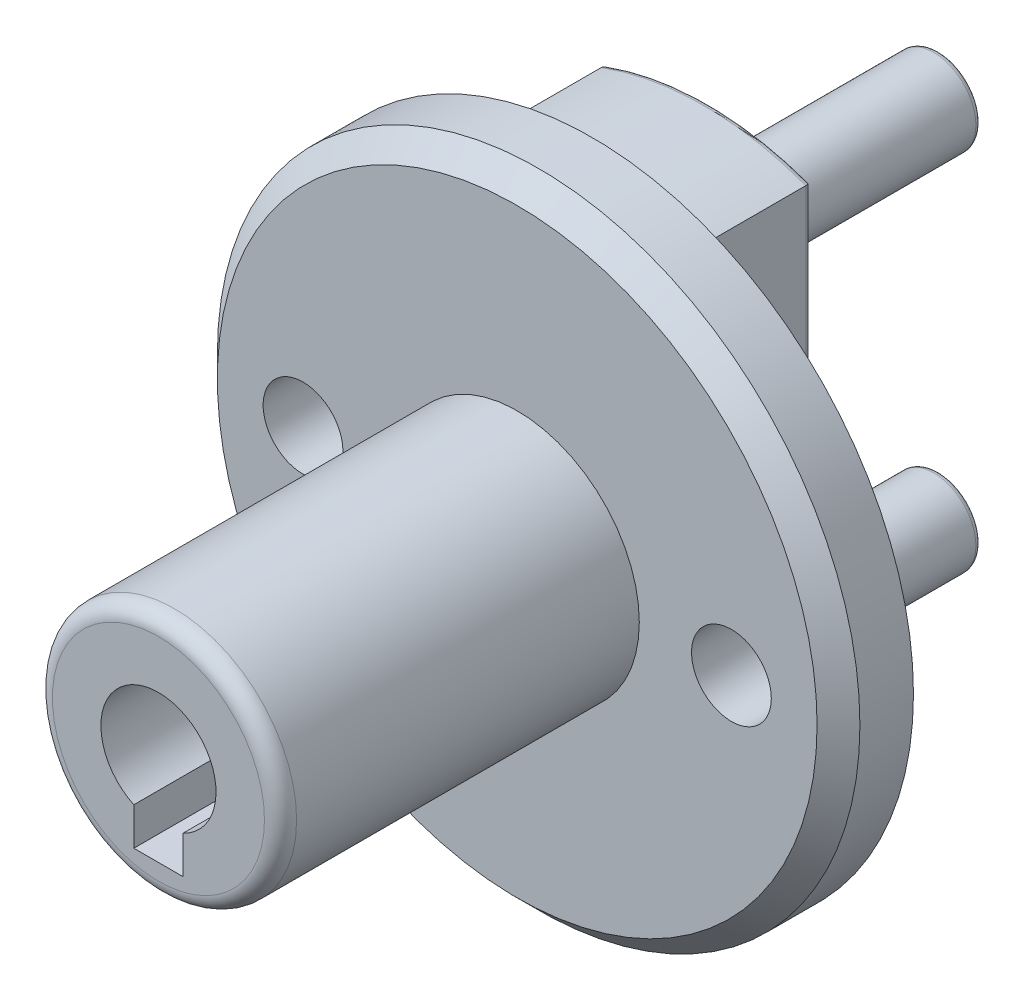
SolidWorks part; units mm, degrees
material "Custom Plastic"
ref_plane "X-Y Datum" through (0, 0, 0) normal (0, 0, 1) x (1, 0, 0)
ref_plane "X-Z Datum" through (0, 0, 0) normal (0, 1, 0) x (1, 0, 0)
ref_plane "Y-Z Datum" through (0, 0, 0) normal (1, 0, 0) x (0, 0, -1)
sketch "Sketch2" plane through (0, 0, 0) normal (0, 0, 1) x (1, 0, 0)
  circle A0 centre (0, 0) radius 30
  dimension "D1" = 60
extrude "Boss-Extrude1" add sketch "Sketch2" along normal blind 7
sketch "Sketch3" plane through (0, 0, 7) normal (0, 0, 1) x (1, 0, 0)
  circle A0 centre (0, 0) radius 11.4
  dimension "D1" = 22.8
extrude "Boss-Extrude2" add sketch "Sketch3" along normal blind 33.5
sketch "Sketch4" plane through (0, 0, 0) normal (0, 0, -1) x (-1, 0, 0)
  line L1 (-9.55, 25.6819) -> (9.55, 25.6819)
  line L2 (-9.55, 25.6819) -> (-9.55, -25.6819)
  line L3 (-9.55, -25.6819) -> (9.55, -25.6819)
  line L4 (9.55, 25.6819) -> (9.55, -25.6819)
  line L5 (-9.55, 25.6819) -> (9.55, -25.6819) construction
  line L6 (-9.55, -25.6819) -> (9.55, 25.6819) construction
  circle A0 centre (0, 0) radius 11.45
  circle A1 centre (0, 0) radius 27.4
  point P0 (0, 0)
  dimension "D2" = 22.9
  dimension "D3" = 54.8
  dimension "D1" = 19.1
extrude "Boss-Extrude3" add sketch "Sketch4" along normal blind 10.9 contours L2 A0 | L4 A0 | L4 A0 L2 | A0 L2 L3 L4 | A0 L4 L1 L2 | L1 A1 | L3 A1
sketch "Sketch5" plane through (0, 0, -10.9) normal (0, 0, -1) x (-1, 0, 0)
  circle A0 centre (0, 0) radius 6.5
  dimension "D1" = 13
extrude "Boss-Extrude4" add sketch "Sketch5" along normal blind 3
sketch "Sketch6" plane through (0, 0, -10.9) normal (0, 0, -1) x (-1, 0, 0)
  line L0 (0, 17) -> (0, -17) construction
  circle A0 centre (0, -17) radius 3.925
  circle A1 centre (0, 17) radius 3.925
  point P5 (0, 0)
  dimension "D2" = 7.85
  dimension "D1" = 34
extrude "Boss-Extrude5" add sketch "Sketch6" along normal blind 21.5
sketch "Sketch7" plane through (0, 0, 7) normal (0, 0, 1) x (1, 0, 0)
  line L0 (20, 0) -> (-20, 0) construction
  circle A0 centre (20, 0) radius 3.725
  circle A1 centre (-20, 0) radius 3.725
  point P5 (0, 0)
  dimension "D1" = 7.45
  dimension "D2" = 40
extrude "Cut-Extrude1" cut sketch "Sketch7" against normal through all
sketch "Sketch8" plane through (0, 0, 40.5) normal (0, 0, 1) x (1, 0, 0)
  line L1 (-2.3, -2.375) -> (2.3, -2.375)
  line L2 (-2.3, -2.375) -> (-2.3, -8.375)
  line L3 (-2.3, -8.375) -> (2.3, -8.375)
  line L4 (2.3, -2.375) -> (2.3, -8.375)
  line L5 (-2.3, -2.375) -> (2.3, -8.375) construction
  line L6 (-2.3, -8.375) -> (2.3, -2.375) construction
  circle A0 centre (0, 0) radius 5.375
  point P3 (0, -5.375)
  dimension "D1" = 10.75
  dimension "D2" = 4.6
  dimension "D3" = 6
extrude "Cut-Extrude2" cut sketch "Sketch8" against normal blind 16.5 contours L4 A0 L2 L1 | L2 A0 L4 L1 | A0 L2 L3 L4
chamfer "Chamfer1" distance 2 angle 45 1 edges at (30, 0, 7)
fillet "Fillet1" radius 1.5 1 edges at (11.4, 0, 40.5)
fillet "Fillet2" radius 0.5 22 edges at (-6.5, 0, -13.9) (-3.925, 17, -32.4) (-3.925, -17, -32.4) (9.55, -15.9992, 0) (9.55, -15.9992, -10.9) (9.55, 15.9992, 0) (9.55, 15.9992, -10.9) (0, -27.4, 0) (0, -27.4, -10.9) (0, 27.4, 0) (0, 27.4, -10.9) (-9.55, -15.9992, 0) (-9.55, -15.9992, -10.9) (-9.55, 15.9992, 0) (-9.55, 15.9992, -10.9) (-11.45, 0, 0) (-11.45, 0, -10.9) (11.45, 0, 0) (11.45, 0, -10.9) (-6.5, 0, -10.9) (-3.925, -17, -10.9) (-3.925, 17, -10.9)
